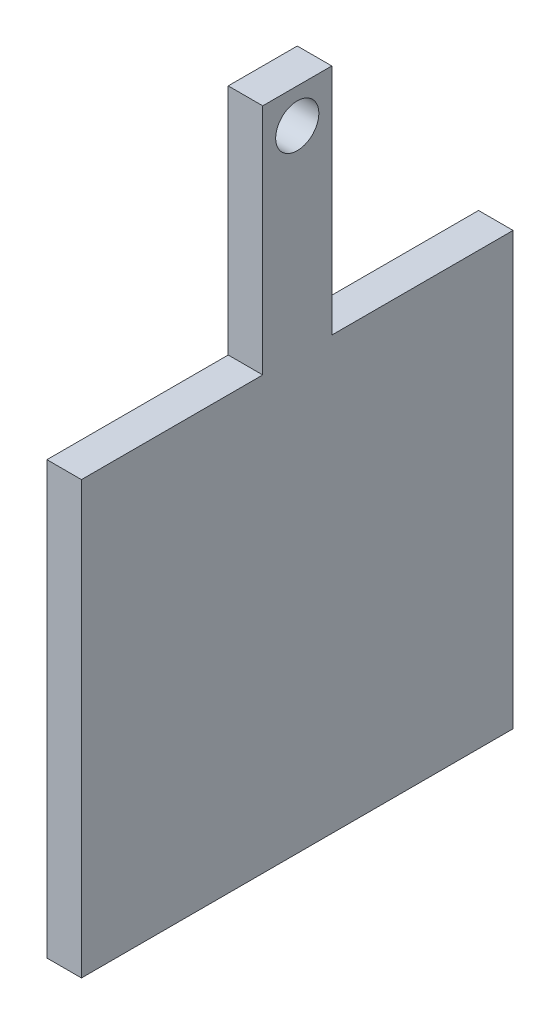
SolidWorks part; units mm, degrees
material "Perspex (TM) GS Acrylic Cast Sheet"
ref_plane "Front Plane" through (0, 0, 0) normal (0, 0, 1) x (1, 0, 0)
ref_plane "Top Plane" through (0, 0, 0) normal (0, 1, 0) x (1, 0, 0)
ref_plane "Right Plane" through (0, 0, 0) normal (1, 0, 0) x (0, 0, -1)
sketch "Sketch1" plane through (0, 0, 0) normal (1, 0, 0) x (0, 0, -1)
  line L0 (0, 0) -> (0, 27)
  line L1 (0, 27) -> (8, 27)
  line L2 (8, 27) -> (8, 0)
  line L3 (8, 0) -> (29, 0)
  line L4 (29, 0) -> (29, -50)
  line L5 (29, -50) -> (-21, -50)
  line L6 (-21, -50) -> (-21, 0)
  line L7 (-21, 0) -> (0, 0)
  circle A0 centre (4, 23) radius 2.5
  point P11 (4, 27)
  dimension "D5" = 5
  dimension "D1" = 21
  dimension "D2" = 27
  dimension "D3" = 8
  dimension "D4" = 50
  dimension "D6" = 4
extrude "Boss-Extrude1" add sketch "Sketch1" along normal blind 4
